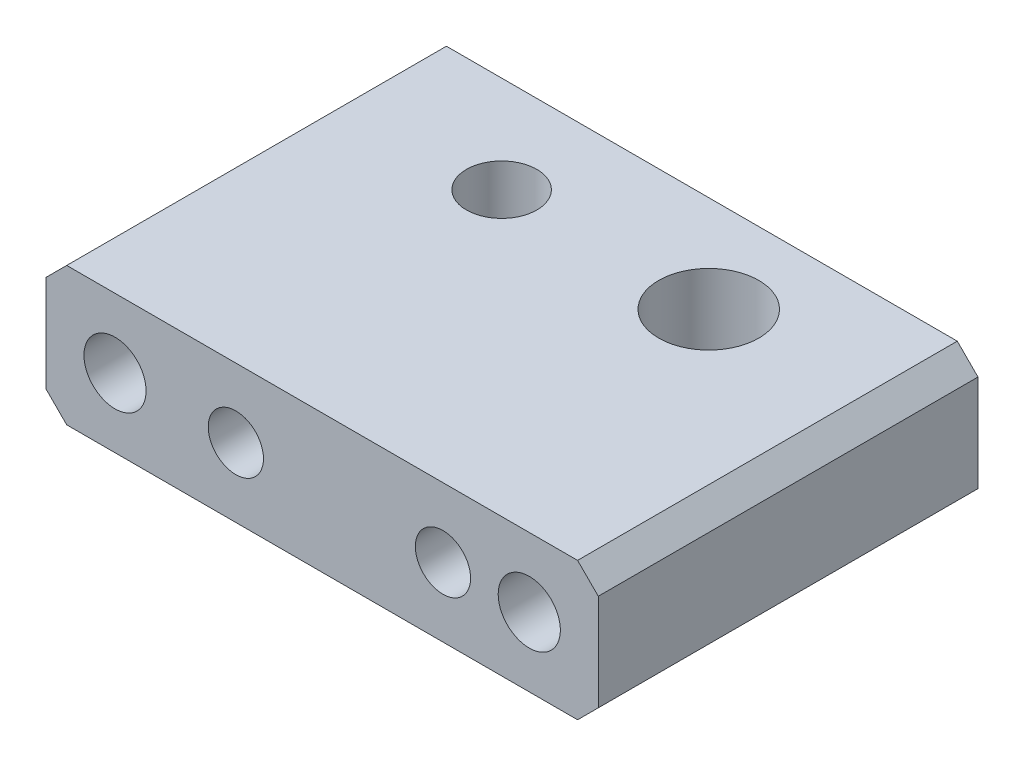
SolidWorks part; units mm, degrees
ref_plane "Front Plane" through (0, 0, 0) normal (0, 0, 1) x (1, 0, 0)
ref_plane "Top Plane" through (0, 0, 0) normal (0, 1, 0) x (1, 0, 0)
ref_plane "Right Plane" through (0, 0, 0) normal (1, 0, 0) x (0, 0, -1)
sketch "Sketch1" plane through (0, 0, 0) normal (0, 1, 0) x (1, 0, 0)
  line L1 (0, 0) -> (80, 0)
  line L2 (0, 0) -> (0, 55)
  line L3 (0, 55) -> (80, 55)
  line L4 (80, 0) -> (80, 55)
  dimension "D1" = 80
  dimension "D2" = 55
extrude "Boss-Extrude1" add sketch "Sketch1" along normal mid plane 20
hole_wizard "M12 Tapped Hole1" positions "Sketch2" profile "Sketch3" tap size "M12" standard "ISO" end condition through all
sketch "Sketch2" plane through (0, 10, 0) normal (0, 1, 0) x (1, 0, 0)
  line L0 (0, 0) -> (80, 0) construction
  line L1 (0, 55) -> (0, 0) construction
  point P0 (25, 41)
  dimension "D1" = 41
  dimension "D2" = 25
cosmetic thread "Hole Thread1" parameters "D2"=12
sketch "Sketch3" plane through (25, 10, -41) normal (1, 0, 0) x (0, 0, 1)
  line L0 (0, 0) -> (0, 20)
  line L1 (0, 20) -> (5.1, 20)
  line L2 (5.1, 20) -> (5.1, 0)
  line L5 (5.1, 0) -> (0, 0)
  line L11 (0, -6.35) -> (0, 107.95) construction
  dimension "Thru Tap Drill Dia." = 10.2
  dimension "Thru Tap Drill Depth" = 20
hole_wizard "M16x1.5 Tapped Hole1" positions "Sketch4" profile "Sketch5" tap size "M16x1.5" standard "KS" end condition through all
sketch "Sketch4" plane through (0, 10, 0) normal (0, 1, 0) x (1, 0, 0)
  line L0 (25, 41) -> (66.5824, 41) construction
  circle A0 centre (25, 41) radius 5.1 construction
  point P0 (55, 41)
  point P9 (55, 41)
  dimension "D1" = 30
cosmetic thread "Hole Thread2"
sketch "Sketch5" plane through (55, 10, -41) normal (1, 0, 0) x (0, 0, 1)
  line L0 (0, 0) -> (0, 20)
  line L1 (0, 20) -> (7.25, 20)
  line L2 (7.25, 20) -> (7.25, 0)
  line L5 (7.25, 0) -> (0, 0)
  line L11 (0, -6.35) -> (0, 107.95) construction
  dimension "Thru Tap Drill Dia." = 14.5
  dimension "Thru Tap Drill Depth" = 20
hole_wizard "CBORE for M8 Hex Socket Head Cap Screw2" positions "Sketch7" profile "Sketch8" counterbore size "M8" standard "ISO" end condition through all
sketch "Sketch7" plane through (0, 0, -55) normal (0, 0, -1) x (-1, 0, 0)
  line L0 (-80, 10) -> (0, 10) construction
  point P0 (-70, 0)
  point P2 (-10, 0)
  point P7 (-40, 10)
  dimension "D1" = 30
  dimension "D2" = 60
sketch "Sketch8" plane through (70, 0, -55) normal (1, 0, 0) x (0, 1, 0)
  line L0 (0, 0) -> (0, 55)
  line L1 (0, 55) -> (4.5, 55)
  line L3 (4.5, 55) -> (4.5, 30)
  line L4 (4.5, 30) -> (7, 30)
  line L5 (7, 30) -> (7, 0)
  line L7 (7, 0) -> (0, 0)
  line L11 (0, -6.35) -> (0, 107.95) construction
  dimension "Thru Hole Dia." = 9
  dimension "Thru Hole Depth" = 55
  dimension "C'Bore Dia." = 14
  dimension "C'Bore Depth" = 30
hole_wizard "Ø8.0 (8) Diameter Hole1" positions "Sketch10" profile "Sketch11" hole size "Ø8.0" standard "ISO"
sketch "Sketch10" plane through (0, 0, 0) normal (0, 0, 1) x (1, 0, 0)
  line L0 (0, 10) -> (80, 10) construction
  point P0 (27.5, 0)
  point P2 (57.5, 0)
  point P7 (40, 10)
  dimension "D1" = 12.5
  dimension "D2" = 30
sketch "Sketch11" plane through (27.5, 0, 0) normal (1, 0, 0) x (0, -1, 0)
  line L0 (0, 0) -> (0, 32.4034)
  line L1 (0, 32.4034) -> (4, 30)
  line L2 (4, 30) -> (4, 0)
  line L5 (4, 0) -> (0, 0)
  line L10 (0, 32.4034) -> (-4, 30) construction
  line L11 (0, -6.35) -> (0, 107.95) construction
  dimension "Hole Dia." = 8
  dimension "Hole Depth" = 30
  dimension "Drill Angle" = 118
chamfer "Chamfer1" distance 3 angle 45 4 edges at (0, -10, -27.5) (80, -10, -27.5) (80, 10, -27.5) (0, 10, -27.5)
